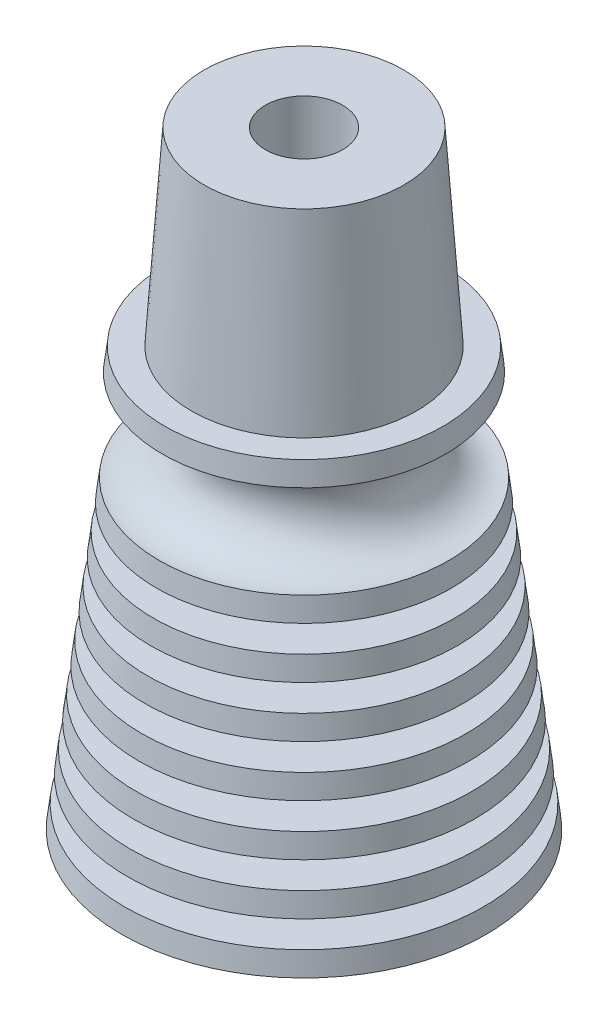
SolidWorks part; units mm, degrees
ref_plane "Front Plane" through (0, 0, 0) normal (0, 0, 1) x (1, 0, 0)
ref_plane "Top Plane" through (0, 0, 0) normal (0, 1, 0) x (1, 0, 0)
ref_plane "Right Plane" through (0, 0, 0) normal (1, 0, 0) x (0, 0, -1)
sketch "Sketch1" plane through (0, 0, 0) normal (0, 0, 1) x (1, 0, 0)
  line L0 (0, 0) -> (0, 30.1625)
  line L1 (0, 0) -> (9.0488, 0)
  line L2 (6.35, 0) -> (4.6291, 13.97) construction
  line L3 (9.0488, 0) -> (7.3279, 13.97) construction
  line L4 (9.0488, 0) -> (8.9111, 1.1176)
  line L5 (8.9111, 1.1176) -> (6.2123, 1.1176)
  line L6 (6.2123, 1.1176) -> (6.0621, 2.3368)
  line L7 (6.0621, 2.3368) -> (8.7609, 2.3368)
  line L8 (8.7609, 2.3368) -> (8.6232, 3.4544)
  line L9 (8.6232, 3.4544) -> (5.9245, 3.4544)
  line L10 (5.9245, 3.4544) -> (5.7743, 4.6736)
  line L11 (5.7743, 4.6736) -> (8.473, 4.6736)
  line L12 (8.473, 4.6736) -> (8.3354, 5.7912)
  line L13 (8.3354, 5.7912) -> (5.6366, 5.7912)
  line L14 (5.6366, 5.7912) -> (5.4864, 7.0104)
  line L15 (5.4864, 7.0104) -> (8.1852, 7.0104)
  line L16 (8.1852, 7.0104) -> (8.0475, 8.128)
  line L17 (8.0475, 8.128) -> (5.3488, 8.128)
  line L18 (5.3488, 8.128) -> (5.1986, 9.3472)
  line L19 (5.1986, 9.3472) -> (7.8973, 9.3472)
  line L20 (7.8973, 9.3472) -> (7.7597, 10.4648)
  line L21 (7.7597, 10.4648) -> (5.0609, 10.4648)
  line L22 (5.0609, 10.4648) -> (4.9107, 11.684)
  line L23 (4.9107, 11.684) -> (7.6095, 11.684)
  line L24 (7.6095, 11.684) -> (7.4718, 12.8016)
  line L25 (7.4718, 12.8016) -> (4.7731, 12.8016)
  line L26 (4.7731, 12.8016) -> (4.6229, 14.0208)
  line L27 (4.6229, 14.0208) -> (7.3216, 14.0208)
  line L28 (7.3216, 14.0208) -> (7.184, 15.1384)
  line L29 (7.184, 15.1384) -> (8.4032, 15.2886) construction
  line L30 (7.0421, 19.6497) -> (6.9045, 20.7673)
  line L31 (6.9045, 20.7673) -> (5.588, 20.7673)
  line L32 (5.588, 20.7673) -> (4.953, 30.1625)
  line L33 (4.953, 30.1625) -> (0, 30.1625)
  arc A0 (7.184, 15.1384) -> (7.0421, 19.6497) centre (6.9069, 17.3876) cw
  point P34 (4.6418, 17.3164)
  dimension "D1" = 30.1625
  dimension "D2" = 6.35
  dimension "D3" = 9.0488
  dimension "D4" = 4.6291
  dimension "D5" = 13.97
  dimension "D6" = 1.1176
  dimension "D7" = 1.2192
  dimension "D8" = 7.0421
  dimension "D9" = 4.6418
  dimension "D10" = 5.588
  dimension "D11" = 4.953
revolve "Revolve1" add sketch "Sketch1" angle 360 about L0
sketch "Sketch2" plane through (0, 30.1625, 0) normal (0, 1, 0) x (1, 0, 0)
  circle A0 centre (0, 0) radius 1.9177
  dimension "D1" = 3.8354
extrude "Cut-Extrude1" cut sketch "Sketch2" against normal through all
